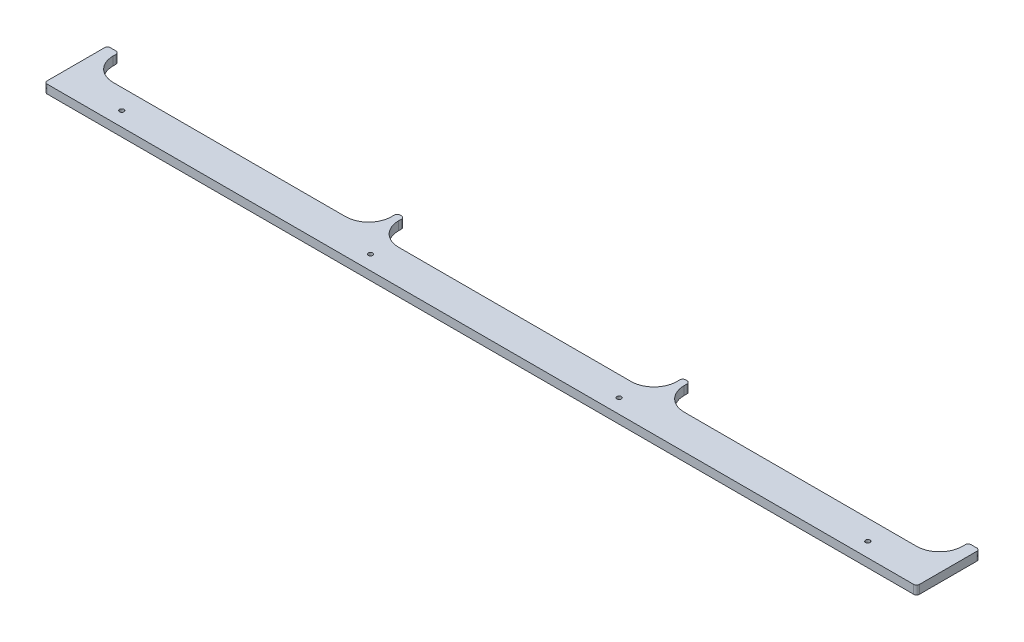
SolidWorks part; units mm, degrees
material "PC High Viscosity"
ref_plane "Front Plane" through (0, 0, 0) normal (0, 0, 1) x (1, 0, 0)
ref_plane "Top Plane" through (0, 0, 0) normal (0, 1, 0) x (1, 0, 0)
ref_plane "Right Plane" through (0, 0, 0) normal (1, 0, 0) x (0, 0, -1)
sketch "Sketch1" plane through (0, 0, 0) normal (0, 1, 0) x (1, 0, 0)
  line L1 (0, 0) -> (965.2, 0)
  line L2 (0, 0) -> (0, 69.85)
  line L4 (965.2, 0) -> (965.2, 69.85)
  line L18 (328.6125, 69.85) -> (328.6125, 63.5)
  line L19 (354.0125, 38.1) -> (611.1875, 38.1)
  line L20 (636.5875, 69.85) -> (636.5875, 63.5)
  line L21 (669.925, 38.1) -> (927.1, 38.1)
  line L22 (644.525, 63.5) -> (644.525, 69.85)
  line L24 (952.5, 63.5) -> (952.5, 69.85)
  line L27 (636.5875, 69.85) -> (644.525, 69.85)
  line L30 (328.6125, 69.85) -> (320.675, 69.85)
  line L31 (952.5, 69.85) -> (965.2, 69.85)
  line L32 (69.85, 15.875) -> (345.0158, 15.875) construction
  line L33 (12.7, 69.85) -> (0, 69.85)
  line L35 (12.7, 69.85) -> (12.7, 63.5)
  line L36 (38.1, 38.1) -> (295.275, 38.1)
  line L37 (320.675, 69.85) -> (320.675, 63.5)
  line L38 (482.6, 0) -> (482.6, 38.1) construction
  arc A0 (328.6125, 63.5) -> (354.0125, 38.1) centre (354.0125, 63.5) ccw
  arc A1 (611.1875, 38.1) -> (636.5875, 63.5) centre (611.1875, 63.5) ccw
  arc A2 (669.925, 38.1) -> (644.525, 63.5) centre (669.925, 63.5) cw
  arc A3 (927.1, 38.1) -> (952.5, 63.5) centre (927.1, 63.5) ccw
  circle A8 centre (69.85, 15.875) radius 2.4574
  circle A9 centre (345.0158, 15.875) radius 2.4575
  arc A11 (295.275, 38.1) -> (320.675, 63.5) centre (295.275, 63.5) ccw
  arc A12 (12.7, 63.5) -> (38.1, 38.1) centre (38.1, 63.5) ccw
  circle A13 centre (895.35, 15.875) radius 2.4574
  circle A14 centre (620.1842, 15.875) radius 2.4575
  point P17 (320.675, 38.1)
  point P34 (12.7, 38.1)
  dimension "D4" = 25.4
  dimension "D5" = 4.9149
  dimension "D18" = 25.4
  dimension "D1" = 965.2
  dimension "D2" = 15.875
  dimension "D3" = 69.85
  dimension "D6" = 307.975
  dimension "D7" = 307.975
  dimension "D8" = 2
  dimension "D9" = 7.9375
  dimension "D10" = 12.7
  dimension "D11" = 38.1
  dimension "D12" = 275.1658
  dimension "D13" = 31.75
  dimension "D14" = 7.9375
  dimension "D15" = 307.975
  dimension "D16" = 69.85
  dimension "D17" = 38.1
  dimension "D19" = 38.1
extrude "Boss-Extrude1" add sketch "Sketch1" along normal blind 9.525
fillet "Fillet1" radius 3.175 10 edges at (0, 4.7625, 0) (965.2, 4.7625, 0) (965.2, 4.7625, -69.85) (952.5, 4.7625, -69.85) (644.525, 4.7625, -69.85) (636.5875, 4.7625, -69.85) (328.6125, 4.7625, -69.85) (12.7, 4.7625, -69.85) (0, 4.7625, -69.85) (320.675, 4.7625, -69.85)
